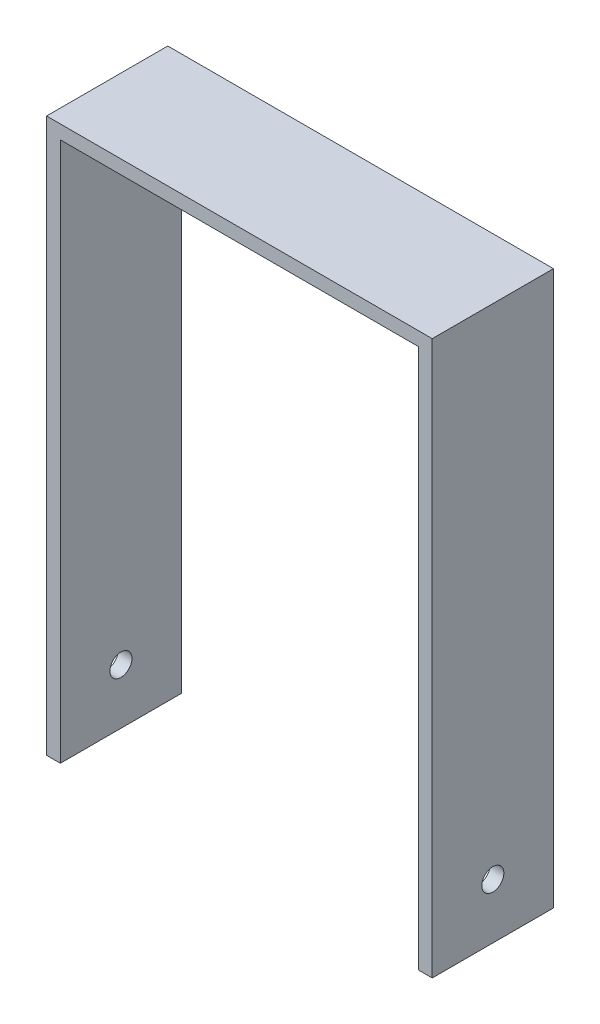
SolidWorks part; units mm, degrees
ref_plane "Alzado" through (0, 0, 0) normal (0, 0, 1) x (1, 0, 0)
ref_plane "Planta" through (0, 0, 0) normal (0, 1, 0) x (1, 0, 0)
ref_plane "Vista lateral" through (0, 0, 0) normal (1, 0, 0) x (0, 0, -1)
sketch "Croquis1" plane through (0, 0, 0) normal (1, 0, 0) x (0, 0, -1)
  line L0 (0, 0) -> (0, 10.5) construction
  line L1 (-6.5652, 4.5714) -> (-1.6413, 11.6429) construction
  line L2 (0, 0) -> (0, -10) construction
  line L3 (1.6413, 11.6429) -> (6.5652, 4.5714) construction
  line L4 (-11, -10) -> (11, -10)
  line L5 (-11, -10) -> (-11, 90.5)
  line L6 (-11, 90.5) -> (11, 90.5)
  line L7 (11, -10) -> (11, 90.5)
  line L8 (0, 0) -> (8, 0) construction
  line L9 (-8.75, 20.5) -> (8.75, 20.5) construction
  line L10 (0, 20.5) -> (0, 10.5) construction
  line L11 (-11, 55.5) -> (11, 55.5) construction
  line L12 (0, 90.5) -> (0, 83) construction
  line L13 (-6.5, 83) -> (6.5, 83) construction
  line L14 (-6.5, 83) -> (-6.5, 60) construction
  line L15 (-6.5, 60) -> (6.5, 60) construction
  line L16 (6.5, 83) -> (6.5, 60) construction
  line L17 (0, 60) -> (0, 55.5) construction
  line L18 (0, 20.5) -> (0, 26.5) construction
  line L19 (-2.75, 31.5) -> (2.75, 31.5) construction
  line L20 (-2.75, 31.5) -> (-2.75, 26.5) construction
  line L21 (-2.75, 26.5) -> (2.75, 26.5) construction
  line L22 (2.75, 31.5) -> (2.75, 26.5) construction
  arc A0 (-6.5652, 4.5714) -> (6.5652, 4.5714) centre (0, 0) ccw construction
  arc A1 (1.6413, 11.6429) -> (-1.6413, 11.6429) centre (0, 10.5) ccw construction
  circle A2 centre (-8.75, 20.5) radius 1.75 construction
  circle A3 centre (8.75, 20.5) radius 1.75 construction
  circle A4 centre (0, 85.25) radius 1 construction
  circle A5 centre (0, 57.75) radius 1 construction
  circle A6 centre (0, 0) radius 2
  dimension "D2" = 4
  dimension "D3" = 16
  dimension "D9" = 3.5
  dimension "D14" = 2
  dimension "D24" = 4
  dimension "D1" = 10.5
  dimension "D4" = 22
  dimension "D5" = 10
  dimension "D6" = 3
  dimension "D7" = 17.5
  dimension "D8" = 20.5
  dimension "D10" = 35
  dimension "D11" = 13
  dimension "D12" = 23
  dimension "D13" = 27.5
  dimension "D15" = 2.25
  dimension "D16" = 2.25
  dimension "D17" = 35
  dimension "D18" = 4.5
  dimension "D19" = 7.5
  dimension "D20" = 100.5
  dimension "D21" = 5.5
  dimension "D22" = 5
  dimension "D23" = 6
extrude "Saliente-Extruir1" add sketch "Croquis1" along normal mid plane 70
sketch "Croquis2" plane through (0, 0, 11) normal (0, 0, 1) x (1, 0, 0)
  line L13 (32.5, -10) -> (32.5, 88)
  line L14 (32.5, 88) -> (-32.5, 88)
  line L15 (-32.5, 88) -> (-32.5, -10)
  line L16 (32.5, -10) -> (32.5, 88)
  line L17 (32.5, 88) -> (-32.5, 88)
  line L18 (-32.5, 88) -> (-32.5, -10)
  dimension "D1" = 2.5
extrude "Cortar-Extruir2" cut sketch "Croquis2" against normal through all and the other way through all
sketch "Croquis3" plane through (0, 0, -11) normal (0, 0, -1) x (-1, 0, 0)
  line L0 (32.5, -10) -> (32.5, 88) construction
  line L1 (-32.5, 88) -> (32.5, 88)
  line L2 (-32.5, 88) -> (-32.5, 75)
  line L3 (-32.5, 75) -> (32.5, 75)
  line L4 (32.5, 88) -> (32.5, 75)
  line L5 (0, 88) -> (0, 75) construction
  circle A0 centre (0, 81.5) radius 2.5
  dimension "D2" = 5
  dimension "D1" = 13
extrude "Saliente-Extruir3" add sketch "Croquis3" against normal blind 3
